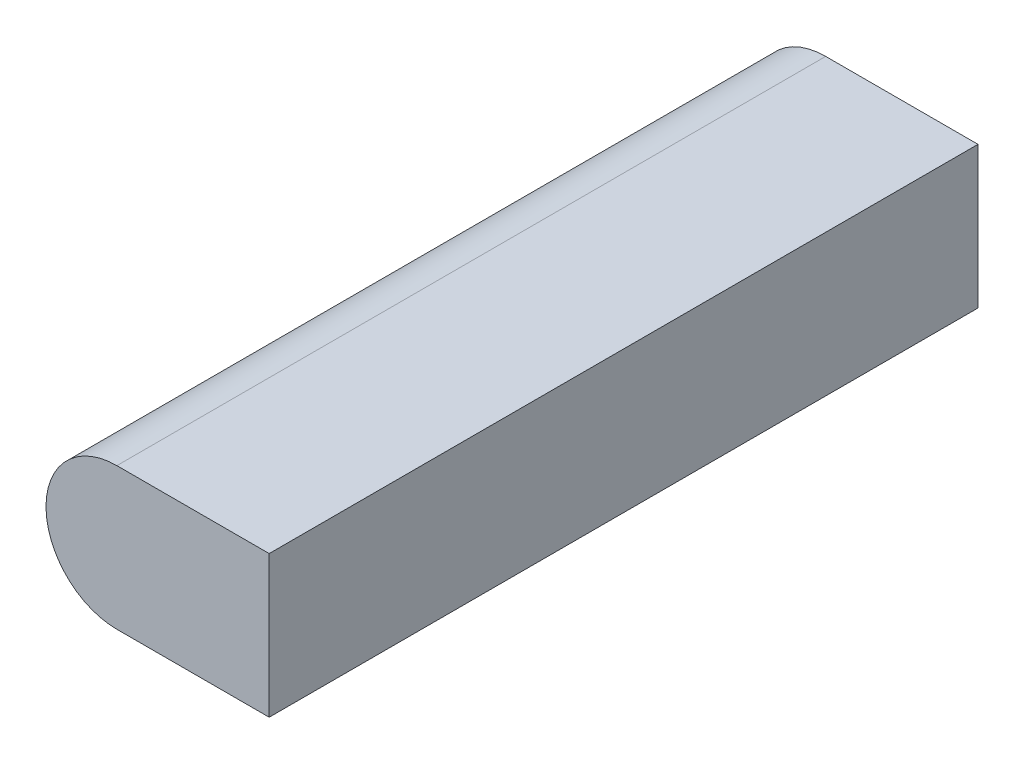
SolidWorks part; units mm, degrees
ref_plane "Front Plane" through (0, 0, 0) normal (0, 0, 1) x (1, 0, 0)
ref_plane "Top Plane" through (0, 0, 0) normal (0, 1, 0) x (1, 0, 0)
ref_plane "Right Plane" through (0, 0, 0) normal (1, 0, 0) x (0, 0, -1)
sketch "Sketch1" plane through (0, 0, 0) normal (0, 0, 1) x (1, 0, 0)
  line L1 (0, 1) -> (2.1488, 1)
  line L2 (2.1488, 1) -> (2.1488, -1)
  line L3 (2.1488, -1) -> (0, -1)
  arc A0 (0, 1) -> (0, -1) centre (0, 0) ccw
  point P6 (0, 0)
  point P7 (0, 0)
  dimension "D1" = 2
extrude "Boss-Extrude1" add sketch "Sketch1" along normal blind 10
